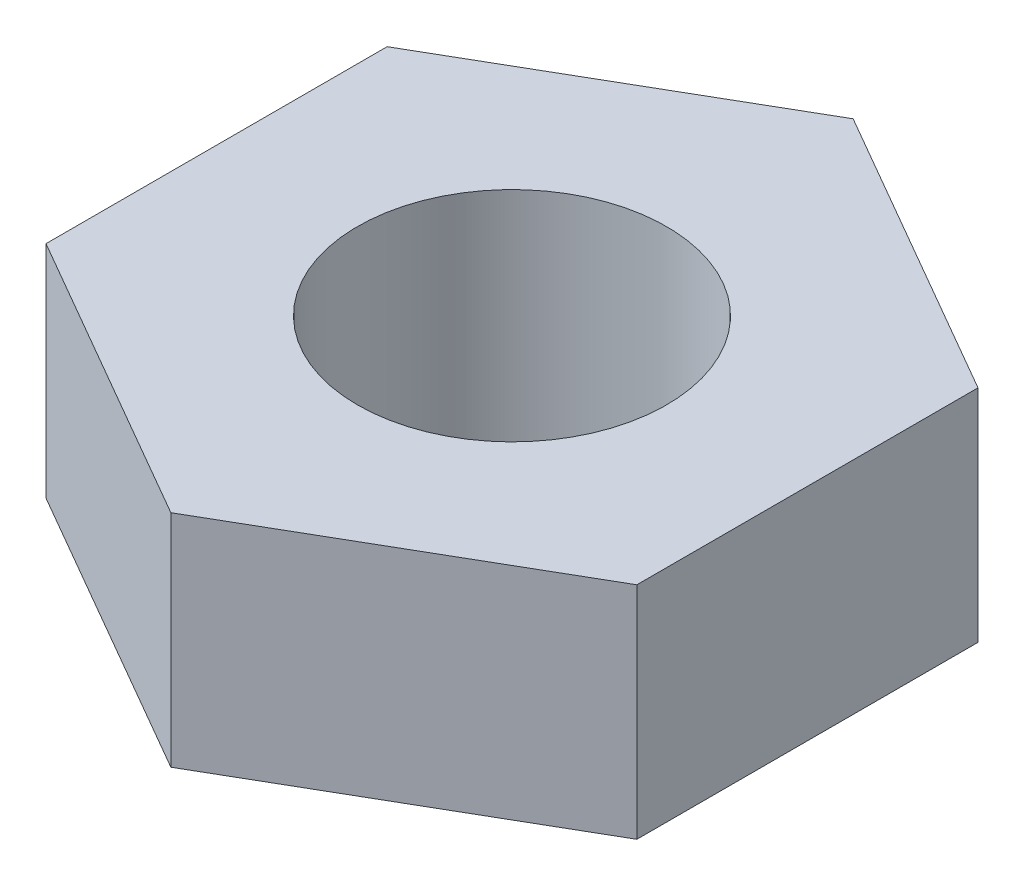
SolidWorks part; units mm, degrees
material "acero"
ref_plane "Alzado" through (0, 0, 0) normal (0, 0, 1) x (1, 0, 0)
ref_plane "Planta" through (0, 0, 0) normal (0, 1, 0) x (1, 0, 0)
ref_plane "Vista lateral" through (0, 0, 0) normal (1, 0, 0) x (0, 0, -1)
sketch "Croquis1" plane through (0, 0, 0) normal (0, 1, 0) x (1, 0, 0)
  line L1 (0, -7.5056) -> (6.5, -3.7528)
  line L2 (6.5, -3.7528) -> (6.5, 3.7528)
  line L3 (6.5, 3.7528) -> (0, 7.5056)
  line L4 (0, 7.5056) -> (-6.5, 3.7528)
  line L5 (-6.5, 3.7528) -> (-6.5, -3.7528)
  line L6 (-6.5, -3.7528) -> (0, -7.5056)
  circle A0 centre (0, 0) radius 6.5 construction
  circle A1 centre (0, 0) radius 3.4
  dimension "D2" = 6.8
  dimension "D1" = 13
extrude "Saliente-Extruir1" add sketch "Croquis1" along normal blind 4.85
